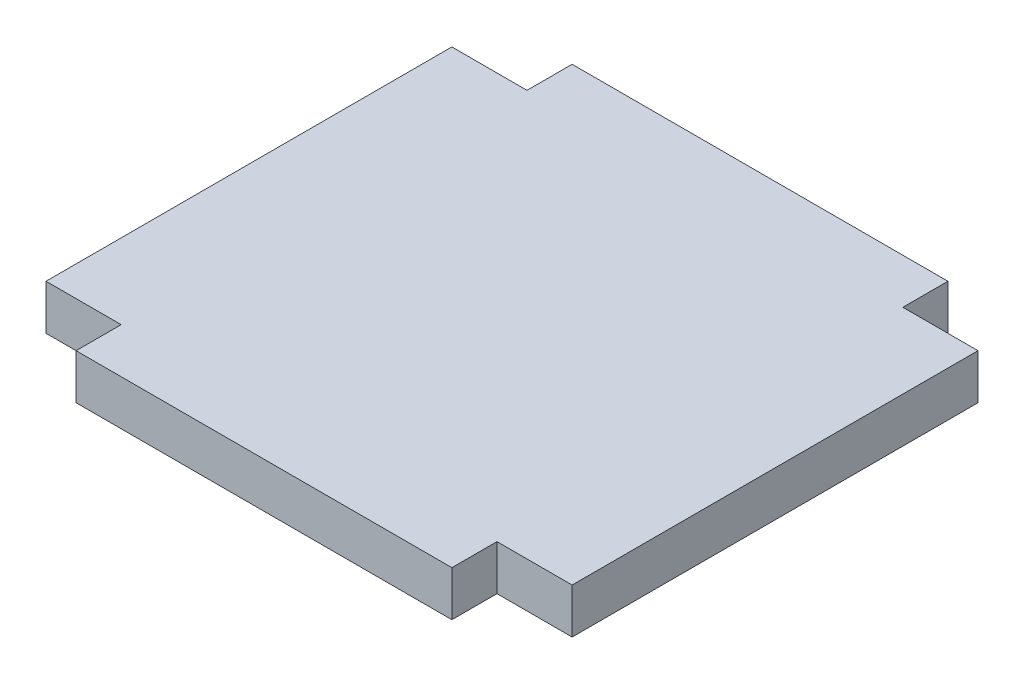
SolidWorks part; units mm, degrees
material "PVC rigido"
ref_plane "Piano frontale" through (0, 0, 0) normal (0, 0, 1) x (1, 0, 0)
ref_plane "Piano superiore" through (0, 0, 0) normal (0, 1, 0) x (1, 0, 0)
ref_plane "Piano destro" through (0, 0, 0) normal (1, 0, 0) x (0, 0, -1)
sketch "Schizzo1" plane through (0, 0, 0) normal (0, 0, 1) x (1, 0, 0)
  line L1 (48, -53) -> (23, -53)
  line L2 (48, -53) -> (48, -56)
  line L3 (48, -56) -> (23, -56)
  line L4 (23, -53) -> (23, -56)
extrude "Estrusione-Estrusione1" add sketch "Schizzo1" along normal up to surface (30 mm away) and the other way up to surface (3 mm away)
ref_plane "Piano1" through (35.5, 0, 0) normal (1, 0, 0) x (0, 0, -1)
sketch "Schizzo2" plane through (48, 0, 0) normal (1, 0, 0) x (0, 0, -1)
  line L0 (-30, -56) -> (3, -56) construction
  line L1 (0, -53) -> (-27, -53)
  line L2 (0, -53) -> (0, -56)
  line L3 (0, -56) -> (-27, -56)
  line L4 (-27, -53) -> (-27, -56)
  line L5 (-27, -56) -> (-27, -53) construction
extrude "Estrusione-Estrusione2" add sketch "Schizzo2" along normal blind 5
mirror "Specchia1" about plane through (35.5, 0, 0) normal (1, 0, 0) of "Estrusione-Estrusione2"
